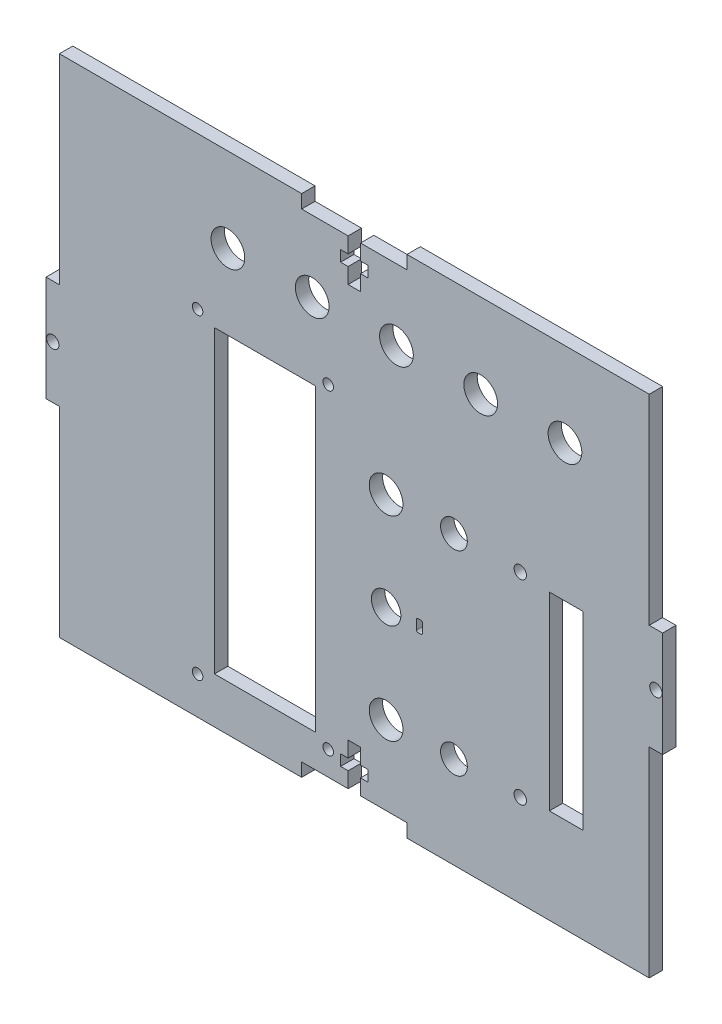
SolidWorks part; units mm, degrees
ref_plane "Front Plane" through (0, 0, 0) normal (0, 0, 1) x (1, 0, 0)
ref_plane "Top Plane" through (0, 0, 0) normal (0, 1, 0) x (1, 0, 0)
ref_plane "Right Plane" through (0, 0, 0) normal (1, 0, 0) x (0, 0, -1)
sketch "Sketch1" plane through (0, 0, 0) normal (0, 0, 1) x (1, 0, 0)
  line L0 (0, 60) -> (0, -60) construction
  line L1 (-70, 60) -> (70, 60)
  line L2 (-70, 60) -> (-70, -60)
  line L3 (-70, -60) -> (70, -60)
  line L4 (70, 60) -> (70, -60)
  line L5 (-70, 60) -> (70, -60) construction
  line L6 (-70, -60) -> (70, 60) construction
  line L7 (-70, 0) -> (70, 0) construction
  line L8 (-3.25, -50.525) -> (3.25, -50.525)
  line L9 (12.5, 60) -> (-12.5, 60)
  line L10 (12.5, 60) -> (12.5, 56.825)
  line L11 (12.5, 56.825) -> (-12.5, 56.825)
  line L12 (-12.5, 60) -> (-12.5, 56.825)
  line L13 (12.5, 60) -> (-12.5, 56.825) construction
  line L14 (12.5, 56.825) -> (-12.5, 60) construction
  line L15 (-1.47, 56.825) -> (1.47, 56.825)
  line L16 (-1.47, 56.825) -> (-1.47, 46.825)
  line L17 (-1.47, 46.825) -> (1.47, 46.825)
  line L18 (1.47, 56.825) -> (1.47, 46.825)
  line L19 (-1.47, 56.825) -> (1.47, 46.825) construction
  line L20 (-1.47, 46.825) -> (1.47, 56.825) construction
  line L21 (-3.25, 53.125) -> (3.25, 53.125)
  line L22 (-3.25, 53.125) -> (-3.25, 50.525)
  line L23 (-3.25, 50.525) -> (3.25, 50.525)
  line L24 (3.25, 53.125) -> (3.25, 50.525)
  line L25 (-3.25, 53.125) -> (3.25, 50.525) construction
  line L26 (-3.25, 50.525) -> (3.25, 53.125) construction
  line L27 (3.25, -53.125) -> (3.25, -50.525)
  line L28 (-3.25, -53.125) -> (3.25, -53.125)
  line L29 (-3.25, -53.125) -> (-3.25, -50.525)
  line L30 (-1.47, -46.825) -> (1.47, -46.825)
  line L31 (1.47, -56.825) -> (1.47, -46.825)
  line L32 (-1.47, -56.825) -> (1.47, -56.825)
  line L33 (-1.47, -56.825) -> (-1.47, -46.825)
  line L34 (12.5, -56.825) -> (-12.5, -56.825)
  line L35 (-12.5, -60) -> (-12.5, -56.825)
  line L36 (12.5, -60) -> (-12.5, -60)
  line L37 (12.5, -60) -> (12.5, -56.825)
  line L38 (73.175, -12.5) -> (70, -12.5)
  line L39 (-73.175, 12.5) -> (-70, 12.5)
  line L40 (-73.175, 12.5) -> (-73.175, -12.5)
  line L41 (-73.175, -12.5) -> (-70, -12.5)
  line L42 (-70, 12.5) -> (-70, -12.5)
  line L43 (-73.175, 12.5) -> (-70, -12.5) construction
  line L44 (-73.175, -12.5) -> (-70, 12.5) construction
  line L45 (70, 12.5) -> (70, -12.5)
  line L46 (73.175, 12.5) -> (70, 12.5)
  line L47 (73.175, 12.5) -> (73.175, -12.5)
  circle A0 centre (-71.5875, 0) radius 1.47
  circle A1 centre (71.5875, 0) radius 1.47
  point P0 (0, 0)
  point P10 (0, 58.4125)
  point P15 (0, 51.825)
  point P20 (0, 51.825)
  point P37 (-71.5875, 0)
  dimension "D11" = 2.94
  dimension "D1" = 120
  dimension "D2" = 140
  dimension "D3" = 3.175
  dimension "D4" = 10
  dimension "D5" = 2.94
  dimension "D6" = 25
  dimension "D7" = 6.5
  dimension "D8" = 2.6
  dimension "D9" = 6.3
  dimension "D10" = 3.175
extrude "Boss-Extrude1" add sketch "Sketch1" along normal mid plane 3.175 contours L21 L24 L23 L18 L17 L16 L22 L11 L12 L1 L2 L3 L4 L10 | L40 L39 L42 L41 | A0 | L38 L45 L46 L47 | A1
sketch "Sketch3" plane through (0, 0, -1.5875) normal (0, 0, -1) x (-1, 0, 0)
  line L0 (-9.6476, 0) -> (-9.6476, -15) construction
  line L5 (-9.6476, -15) -> (-19.2951, -15) construction
  line L6 (-50.3, 7.5) -> (-50.3, -22.5) construction
  line L7 (-46.3, 7.5) -> (-54.3, 7.5)
  line L8 (-46.3, 7.5) -> (-46.3, -37.5)
  line L9 (-46.3, -37.5) -> (-54.3, -37.5)
  line L10 (-54.3, 7.5) -> (-54.3, -37.5)
  line L11 (-48.7125, -38.0096) -> (-48.7125, -21.9577) construction
  line L12 (-51.8875, -21.9577) -> (-51.8875, -38.0096) construction
  line L13 (0, 0) -> (-19.2951, 0) construction
  dimension "D1" = 8
  dimension "D2" = 45
  dimension "D3" = 15
extrude "Cut-Extrude1" cut sketch "Sketch3" against normal through all
sketch "Sketch4" plane through (0, 0, -1.5875) normal (0, 0, -1) x (-1, 0, 0)
  line L0 (33.2, 21.2555) -> (33.2, -48.2445) construction
  line L1 (33.2, 22.1055) -> (9.2, 22.1055)
  line L2 (33.2, 22.1055) -> (33.2, -49.0945)
  line L3 (33.2, -49.0945) -> (9.2, -49.0945)
  line L4 (9.2, 22.1055) -> (9.2, -49.0945)
  line L5 (9.2, -48.2445) -> (9.2, 21.2555) construction
  line L6 (10.05, 22.1055) -> (16.7, 22.1055) construction
  line L7 (32.35, -49.0945) -> (10.05, -49.0945) construction
extrude "Cut-Extrude2" cut sketch "Sketch4" against normal through all
sketch "Sketch5" plane through (0, 0, -1.5875) normal (0, 0, -1) x (-1, 0, 0)
  line L0 (-15.1534, -16.25) -> (-15.7792, -16.25) construction
  line L1 (-15.7792, -13.75) -> (-15.1534, -13.75) construction
  line L2 (-14.9534, -13.95) -> (-14.9534, -16.05) construction
  line L3 (-15.1534, -16.25) -> (-15.7792, -16.25)
  line L4 (-15.7792, -13.75) -> (-15.1534, -13.75)
  line L5 (-14.9534, -13.95) -> (-14.9534, -16.05)
  line L6 (-15.1534, -16.45) -> (-15.7792, -16.45)
  line L7 (-15.7792, -13.55) -> (-15.1534, -13.55)
  line L8 (-14.7534, -13.95) -> (-14.7534, -16.05)
  arc A0 (-15.1534, -16.25) -> (-14.9534, -16.05) centre (-15.1534, -16.05) ccw construction
  arc A1 (-15.9775, -16.0753) -> (-15.7792, -16.25) centre (-15.7792, -16.05) ccw construction
  arc A2 (-15.9775, -13.9247) -> (-15.9775, -16.0753) centre (-7.5458, -15) ccw construction
  arc A3 (-15.7792, -13.75) -> (-15.9775, -13.9247) centre (-15.7792, -13.95) ccw construction
  arc A4 (-14.9534, -13.95) -> (-15.1534, -13.75) centre (-15.1534, -13.95) ccw construction
  arc A5 (-15.1534, -16.25) -> (-14.9534, -16.05) centre (-15.1534, -16.05) ccw
  arc A6 (-15.9775, -16.0753) -> (-15.7792, -16.25) centre (-15.7792, -16.05) ccw
  arc A7 (-15.9775, -13.9247) -> (-15.9775, -16.0753) centre (-7.5458, -15) ccw
  arc A8 (-15.7792, -13.75) -> (-15.9775, -13.9247) centre (-15.7792, -13.95) ccw
  arc A9 (-14.9534, -13.95) -> (-15.1534, -13.75) centre (-15.1534, -13.95) ccw
  arc A10 (-16.1759, -16.1006) -> (-15.7792, -16.45) centre (-15.7792, -16.05) ccw
  arc A11 (-16.1759, -13.8994) -> (-16.1759, -16.1006) centre (-7.5458, -15) ccw
  arc A12 (-15.7792, -13.55) -> (-16.1759, -13.8994) centre (-15.7792, -13.95) ccw
  arc A13 (-14.7534, -13.95) -> (-15.1534, -13.55) centre (-15.1534, -13.95) ccw
  arc A14 (-15.1534, -16.45) -> (-14.7534, -16.05) centre (-15.1534, -16.05) ccw
  dimension "D1" = 0.2
extrude "Cut-Extrude4" cut sketch "Sketch5" against normal through all contours L8 A14 L6 A10 A11 A12 L7 A13
sketch "Sketch6" plane through (0, 0, -1.5875) normal (0, 0, -1) x (-1, 0, 0)
  line L0 (-70, 40) -> (70, 40) construction
  line L1 (-70, 56.825) -> (-70, 12.5) construction
  line L2 (70, 60) -> (70, 12.5) construction
  line L3 (70, 60) -> (12.5, 60) construction
  line L4 (-50, 40) -> (-30, 40)
  line L5 (-30, 40) -> (-10, 40)
  line L6 (-10, 40) -> (10, 40)
  line L7 (10, 40) -> (30, 40)
  line L8 (-70, 60) -> (-70, 12.5) construction
  line L9 (-10, 40) -> (10, 40)
  line L10 (-30, 40) -> (-10, 40)
  line L11 (-50, 40) -> (-30, 40)
  line L12 (-70, 40) -> (-50, 40)
  circle A0 centre (30, 40) radius 4
  circle A1 centre (10, 40) radius 4
  circle A2 centre (-10, 40) radius 4
  circle A3 centre (-30, 40) radius 4
  circle A4 centre (-50, 40) radius 4
  dimension "D4" = 8
  dimension "D1" = 20
  dimension "D2" = 20
  dimension "D3" = 20
  dimension "D5" = 5
extrude "Cut-Extrude5" cut sketch "Sketch6" against normal through all contours A0 | A1 | A2 | A3 | A4
sketch "Sketch9" plane through (0, 0, 1.5875) normal (0, 0, 1) x (1, 0, 0)
  circle A0 centre (-37.2, 23.9055) radius 1.25 construction
  circle A1 centre (-6.2, 23.9055) radius 1.25 construction
  circle A2 centre (-6.2, -51.0945) radius 1.25 construction
  circle A3 centre (-37.2, -51.0945) radius 1.25 construction
  circle A4 centre (-37.2, 23.9055) radius 1.25
  circle A5 centre (-6.2, 23.9055) radius 1.25
  circle A6 centre (-6.2, -51.0945) radius 1.25
  circle A7 centre (-37.2, -51.0945) radius 1.25
  circle A8 centre (39.3875, 8.1613) radius 1.47 construction
  circle A9 centre (39.3875, -38.1613) radius 1.47 construction
  circle A10 centre (39.3875, 8.1613) radius 1.47
  circle A11 centre (39.3875, -38.1613) radius 1.47
extrude "Cut-Extrude6" cut sketch "Sketch9" against normal through all
sketch "Sketch10" plane through (0, 0, -1.5875) normal (0, 0, -1) x (-1, 0, 0)
  line L1 (-23.65, 8.1613) -> (-37.9175, 8.1613) construction
  line L2 (-23.65, -38.1613) -> (-37.9175, -38.1613) construction
  line L3 (-33.65, 28.1613) -> (-33.65, -11.8387) construction
  line L4 (50, 60) -> (50, -60) construction
  line L5 (70, 60) -> (12.5, 60) construction
  line L6 (70, -60) -> (12.5, -60) construction
  line L7 (70, 60) -> (70, 12.5) construction
  line L8 (-33.65, -18.1613) -> (-33.65, -58.1613) construction
  line L9 (-23.65, 8.1613) -> (-16.825, 8.1613) construction
  line L10 (-16.825, 28.1613) -> (-16.825, -11.8387) construction
  line L11 (-23.65, -38.1613) -> (-16.825, -38.1613) construction
  line L12 (-16.825, -18.1613) -> (-16.825, -58.1613) construction
  circle A0 centre (-39.3875, 8.1613) radius 1.47 construction
  circle A1 centre (-39.3875, -38.1613) radius 1.47 construction
  dimension "D1" = 20
  dimension "D2" = 10
  dimension "D3" = 6.825
  dimension "D4" = 40
  dimension "D5" = 40
  dimension "D6" = 6.825
  dimension "D7" = 10
  dimension "D8" = 40
  dimension "D9" = 40
sketch "Sketch11" plane through (0, 0, -1.5875) normal (0, 0, -1) x (-1, 0, 0)
  text T0 "Alden Dent PID Box" font "Century Gothic" height 9
  text T1 "Power Off" font "Century Gothic" height 3.175
  text T2 "PID Off" font "Century Gothic" height 3.175
  text T3 "Power On" font "Century Gothic" height 3.175
  text T4 "PID On" font "Century Gothic" height 3.175
sketch "Sketch12" plane through (0, 0, -1.5875) normal (0, 0, -1) x (-1, 0, 0)
  circle A1 centre (-7.5458, -38.1613) radius 4
  circle A2 centre (-7.5458, 8.1613) radius 4
  circle A3 centre (-7.5458, -15) radius 3.5
  arc A6 (-21.105, 10.0596) -> (-21.105, 6.2629) centre (-23.65, 8.1613) ccw construction
  circle A10 centre (-23.65, -38.1613) radius 3.175
  circle A11 centre (-23.65, 8.1613) radius 3.175
  dimension "D1" = 7
  dimension "D2" = 8
  dimension "D3" = 6.35
extrude "Cut-Extrude7" cut sketch "Sketch12" against normal through all
